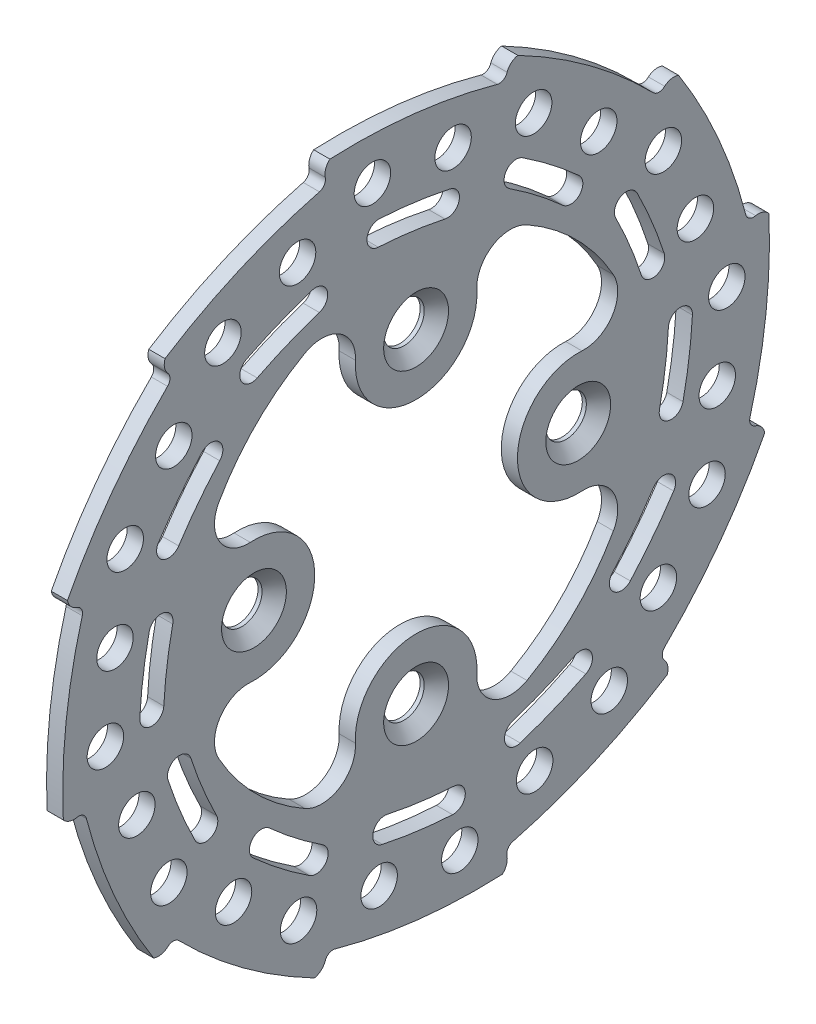
SolidWorks part; units mm, degrees
ref_plane "Front Plane" through (0, 0, 0) normal (0, 0, 1) x (1, 0, 0)
ref_plane "Top Plane" through (0, 0, 0) normal (0, 1, 0) x (1, 0, 0)
ref_plane "Right Plane" through (0, 0, 0) normal (1, 0, 0) x (0, 0, -1)
ref_plane "Plane1" through (4, 0, 0) normal (1, 0, 0) x (0, 0, -1)
sketch "Sketch1" plane through (4, 0, 0) normal (1, 0, 0) x (0, 0, -1)
  line L0 (-83.4912, 22.3714) -> (-83.7497, 22.4407)
  line L1 (-83.4912, -22.3714) -> (-83.7497, -22.4407)
  line L2 (-61.1198, -61.1198) -> (-61.3091, -61.3091)
  line L3 (-22.3714, -83.4912) -> (-22.4407, -83.7497)
  line L4 (22.3714, -83.4912) -> (22.4407, -83.7497)
  line L5 (61.1198, -61.1198) -> (61.3091, -61.3091)
  line L6 (83.4912, -22.3714) -> (83.7497, -22.4407)
  line L7 (83.4912, 22.3714) -> (83.7497, 22.4407)
  line L8 (61.1198, 61.1198) -> (61.3091, 61.3091)
  line L9 (22.3714, 83.4912) -> (22.4407, 83.7497)
  line L10 (-22.3714, 83.4912) -> (-22.4407, 83.7497)
  line L11 (-61.1198, 61.1198) -> (-61.3091, 61.3091)
  line L12 (0, 0) -> (-69.3199, -69.3199) construction
  circle A0 centre (40, 0) radius 5
  circle A1 centre (0, -40) radius 5
  circle A2 centre (-40, 0) radius 5
  circle A3 centre (-71.773, 28.9982) radius 4.5
  arc A4 (-52.8492, 40.1536) -> (-48.4456, 36.1774) centre (-50.6474, 38.1655) cw
  arc A5 (-48.4456, 36.1774) -> (-58.5717, 23.0439) centre (30.9131, -35.4797) ccw
  arc A6 (-58.5717, 23.0439) -> (-63.5372, 26.2913) centre (-61.0545, 24.6676) cw
  arc A7 (-63.5372, 26.2913) -> (-52.8492, 40.1536) centre (30.9131, -35.4797) cw
  circle A8 centre (-59.7785, 45.0463) radius 4.5
  circle A9 centre (-47.6581, 60.9996) radius 4.5
  arc A10 (-25.6919, 61.1987) -> (-23.8664, 55.5533) centre (-24.7791, 58.376) cw
  arc A11 (-23.8664, 55.5533) -> (-39.2027, 49.2424) centre (9.0317, -46.1828) ccw
  arc A12 (-39.2027, 49.2424) -> (-41.8792, 54.5376) centre (-40.5409, 51.89) cw
  arc A13 (-41.8792, 54.5376) -> (-25.6919, 61.1987) centre (9.0317, -46.1828) cw
  circle A14 centre (-29.2465, 68.9005) radius 4.5
  circle A15 centre (-10.7733, 76.6563) radius 4.5
  arc A16 (8.3495, 65.8455) -> (7.1078, 60.0438) centre (7.7286, 62.9447) cw
  arc A17 (7.1078, 60.0438) -> (-9.3293, 62.2465) centre (-15.2698, -44.5113) ccw
  arc A18 (-9.3293, 62.2465) -> (-8.9996, 68.1705) centre (-9.1645, 65.2085) cw
  arc A19 (-8.9996, 68.1705) -> (8.3495, 65.8455) centre (-15.2698, -44.5113) cw
  circle A20 centre (9.122, 74.2929) radius 4.5
  circle A21 centre (28.9982, 71.773) radius 4.5
  arc A22 (40.1536, 52.8492) -> (36.1774, 48.4456) centre (38.1655, 50.6474) cw
  arc A23 (36.1774, 48.4456) -> (23.0439, 58.5717) centre (-35.4797, -30.9131) ccw
  arc A24 (23.0439, 58.5717) -> (26.2913, 63.5372) centre (24.6676, 61.0545) cw
  arc A25 (26.2913, 63.5372) -> (40.1536, 52.8492) centre (-35.4797, -30.9131) cw
  circle A26 centre (45.0463, 59.7785) radius 4.5
  circle A27 centre (60.9996, 47.6581) radius 4.5
  arc A28 (61.1987, 25.6919) -> (55.5533, 23.8664) centre (58.376, 24.7791) cw
  arc A29 (55.5533, 23.8664) -> (49.2424, 39.2027) centre (-46.1828, -9.0317) ccw
  arc A30 (49.2424, 39.2027) -> (54.5376, 41.8792) centre (51.89, 40.5409) cw
  arc A31 (54.5376, 41.8792) -> (61.1987, 25.6919) centre (-46.1828, -9.0317) cw
  circle A32 centre (68.9005, 29.2465) radius 4.5
  circle A33 centre (76.6563, 10.7733) radius 4.5
  arc A34 (65.8455, -8.3495) -> (60.0438, -7.1078) centre (62.9447, -7.7286) cw
  arc A35 (60.0438, -7.1078) -> (62.2465, 9.3293) centre (-44.5113, 15.2698) ccw
  arc A36 (62.2465, 9.3293) -> (68.1705, 8.9996) centre (65.2085, 9.1645) cw
  arc A37 (68.1705, 8.9996) -> (65.8455, -8.3495) centre (-44.5113, 15.2698) cw
  circle A38 centre (74.2929, -9.122) radius 4.5
  circle A39 centre (71.773, -28.9982) radius 4.5
  arc A40 (52.8492, -40.1536) -> (48.4456, -36.1774) centre (50.6474, -38.1655) cw
  arc A41 (48.4456, -36.1774) -> (58.5717, -23.0439) centre (-30.9131, 35.4797) ccw
  arc A42 (58.5717, -23.0439) -> (63.5372, -26.2913) centre (61.0545, -24.6676) cw
  arc A43 (63.5372, -26.2913) -> (52.8492, -40.1536) centre (-30.9131, 35.4797) cw
  circle A44 centre (59.7785, -45.0463) radius 4.5
  circle A45 centre (47.6581, -60.9996) radius 4.5
  arc A46 (25.6919, -61.1987) -> (23.8664, -55.5533) centre (24.7791, -58.376) cw
  arc A47 (23.8664, -55.5533) -> (39.2027, -49.2424) centre (-9.0317, 46.1828) ccw
  arc A48 (39.2027, -49.2424) -> (41.8792, -54.5376) centre (40.5409, -51.89) cw
  arc A49 (41.8792, -54.5376) -> (25.6919, -61.1987) centre (-9.0317, 46.1828) cw
  circle A50 centre (29.2465, -68.9005) radius 4.5
  circle A51 centre (10.7733, -76.6563) radius 4.5
  arc A52 (-8.3495, -65.8455) -> (-7.1078, -60.0438) centre (-7.7286, -62.9447) cw
  arc A53 (-7.1078, -60.0438) -> (9.3293, -62.2465) centre (15.2698, 44.5113) ccw
  arc A54 (9.3293, -62.2465) -> (8.9996, -68.1705) centre (9.1645, -65.2085) cw
  arc A55 (8.9996, -68.1705) -> (-8.3495, -65.8455) centre (15.2698, 44.5113) cw
  circle A56 centre (-9.122, -74.2929) radius 4.5
  circle A57 centre (-28.9982, -71.773) radius 4.5
  arc A58 (-40.1536, -52.8492) -> (-36.1774, -48.4456) centre (-38.1655, -50.6474) cw
  arc A59 (-36.1774, -48.4456) -> (-23.0439, -58.5717) centre (35.4797, 30.9131) ccw
  arc A60 (-23.0439, -58.5717) -> (-26.2913, -63.5372) centre (-24.6676, -61.0545) cw
  arc A61 (-26.2913, -63.5372) -> (-40.1536, -52.8492) centre (35.4797, 30.9131) cw
  circle A62 centre (-45.0463, -59.7785) radius 4.5
  circle A63 centre (-60.9996, -47.6581) radius 4.5
  arc A64 (-54.5376, -41.8792) -> (-61.1987, -25.6919) centre (46.1828, 9.0317) cw
  arc A65 (-61.1987, -25.6919) -> (-55.5533, -23.8664) centre (-58.376, -24.7791) cw
  arc A66 (-55.5533, -23.8664) -> (-49.2424, -39.2027) centre (46.1828, 9.0317) ccw
  arc A67 (-49.2424, -39.2027) -> (-54.5376, -41.8792) centre (-51.89, -40.5409) cw
  circle A68 centre (-68.9005, -29.2465) radius 4.5
  arc A69 (-65.8455, 8.3495) -> (-60.0438, 7.1078) centre (-62.9447, 7.7286) cw
  arc A70 (-60.0438, 7.1078) -> (-62.2465, -9.3293) centre (44.5113, -15.2698) ccw
  arc A71 (-62.2465, -9.3293) -> (-68.1705, -8.9996) centre (-65.2085, -9.1645) cw
  arc A72 (-68.1705, -8.9996) -> (-65.8455, 8.3495) centre (44.5113, -15.2698) cw
  circle A73 centre (-76.6563, -10.7733) radius 4.5
  circle A74 centre (-74.2929, 9.122) radius 4.5
  circle A75 centre (0, 40) radius 5
  circle A76 centre (40, 0) radius 15
  arc A77 (-40.9088, 14.9724) -> (-48.6744, 27.3701) centre (-41.4135, 23.2872) cw
  arc A78 (-48.6744, 27.3701) -> (-27.3701, 48.6744) centre (0, 0) cw
  arc A79 (-14.9724, 40.9088) -> (-27.3701, 48.6744) centre (-23.2872, 41.4135) ccw
  circle A80 centre (0, -40) radius 15
  arc A81 (-14.9724, -40.9088) -> (-27.3701, -48.6744) centre (-23.2872, -41.4135) cw
  arc A82 (-27.3701, -48.6744) -> (-48.6744, -27.3701) centre (0, 0) cw
  arc A83 (14.9724, 40.9088) -> (27.3701, 48.6744) centre (23.2872, 41.4135) cw
  circle A84 centre (-40, 0) radius 15
  arc A85 (27.3701, 48.6744) -> (48.6744, 27.3701) centre (0, 0) cw
  arc A86 (40.9088, 14.9724) -> (48.6744, 27.3701) centre (41.4135, 23.2872) ccw
  arc A87 (40.9088, -14.9724) -> (48.6744, -27.3701) centre (41.4135, -23.2872) cw
  arc A88 (-40.9088, -14.9724) -> (-48.6744, -27.3701) centre (-41.4135, -23.2872) ccw
  arc A89 (48.6744, -27.3701) -> (27.3701, -48.6744) centre (0, 0) cw
  arc A90 (14.9724, -40.9088) -> (27.3701, -48.6744) centre (23.2872, -41.4135) ccw
  arc A92 (-86.0187, 25.093) -> (-83.4912, 22.3714) centre (-82.5871, 25.7454) ccw
  arc A93 (-83.7497, 22.4407) -> (-82.3634, 20.0131) centre (-84.259, 20.5402) cw
  arc A94 (-82.3634, 20.0131) -> (-87.0409, -21.2781) centre (44.5113, -15.2698) ccw
  arc A95 (-87.0409, -21.2781) -> (-83.4912, -22.3714) centre (-84.3952, -18.9974) ccw
  arc A96 (-83.7497, -22.4407) -> (-81.3354, -23.8499) centre (-83.2405, -24.3411) cw
  arc A97 (-81.3354, -23.8499) -> (-64.7405, -61.9478) centre (46.1828, 9.0317) ccw
  arc A98 (-64.7405, -61.9478) -> (-61.1198, -61.1198) centre (-63.5897, -58.6498) ccw
  arc A99 (-61.3091, -61.3091) -> (-58.5136, -61.3223) centre (-59.9178, -62.7003) cw
  arc A100 (-58.5136, -61.3223) -> (-25.093, -86.0187) centre (35.4797, 30.9131) ccw
  arc A101 (-25.093, -86.0187) -> (-22.3714, -83.4912) centre (-25.7454, -82.5871) ccw
  arc A102 (-22.4407, -83.7497) -> (-20.0131, -82.3634) centre (-20.5402, -84.259) cw
  arc A103 (-20.0131, -82.3634) -> (21.2781, -87.0409) centre (15.2698, 44.5113) ccw
  arc A104 (21.2781, -87.0409) -> (22.3714, -83.4912) centre (18.9974, -84.3952) ccw
  arc A105 (22.4407, -83.7497) -> (23.8499, -81.3354) centre (24.3411, -83.2405) cw
  arc A106 (23.8499, -81.3354) -> (61.9478, -64.7405) centre (-9.0317, 46.1828) ccw
  arc A107 (61.9478, -64.7405) -> (61.1198, -61.1198) centre (58.6498, -63.5897) ccw
  arc A108 (61.3091, -61.3091) -> (61.3223, -58.5136) centre (62.7003, -59.9178) cw
  arc A109 (61.3223, -58.5136) -> (86.0187, -25.093) centre (-30.9131, 35.4797) ccw
  arc A110 (86.0187, -25.093) -> (83.4912, -22.3714) centre (82.5871, -25.7454) ccw
  arc A111 (83.7497, -22.4407) -> (82.3634, -20.0131) centre (84.259, -20.5402) cw
  arc A112 (82.3634, -20.0131) -> (87.0409, 21.2781) centre (-44.5113, 15.2698) ccw
  arc A113 (87.0409, 21.2781) -> (83.4912, 22.3714) centre (84.3952, 18.9974) ccw
  arc A114 (83.7497, 22.4407) -> (81.3354, 23.8499) centre (83.2405, 24.3411) cw
  arc A115 (81.3354, 23.8499) -> (64.7405, 61.9478) centre (-46.1828, -9.0317) ccw
  arc A116 (64.7405, 61.9478) -> (61.1198, 61.1198) centre (63.5897, 58.6498) ccw
  arc A117 (61.3091, 61.3091) -> (58.5136, 61.3223) centre (59.9178, 62.7003) cw
  arc A118 (58.5136, 61.3223) -> (25.093, 86.0187) centre (-35.4797, -30.9131) ccw
  arc A119 (25.093, 86.0187) -> (22.3714, 83.4912) centre (25.7454, 82.5871) ccw
  arc A120 (22.4407, 83.7497) -> (20.0131, 82.3634) centre (20.5402, 84.259) cw
  arc A121 (20.0131, 82.3634) -> (-21.2781, 87.0409) centre (-15.2698, -44.5113) ccw
  arc A122 (-21.2781, 87.0409) -> (-22.3714, 83.4912) centre (-18.9974, 84.3952) ccw
  arc A123 (-22.4407, 83.7497) -> (-23.8499, 81.3354) centre (-24.3411, 83.2405) cw
  arc A124 (-23.8499, 81.3354) -> (-61.9478, 64.7405) centre (9.0317, -46.1828) ccw
  arc A125 (-61.9478, 64.7405) -> (-61.1198, 61.1198) centre (-58.6498, 63.5897) ccw
  arc A126 (-61.3091, 61.3091) -> (-61.3223, 58.5136) centre (-62.7003, 59.9178) cw
  arc A127 (-61.3223, 58.5136) -> (-86.0187, 25.093) centre (30.9131, -35.4797) ccw
  circle A128 centre (0, 40) radius 15
  point P247 (0, 0)
  point P253 (0, 0)
  dimension "D2" = 4
  dimension "D5" = 10
  dimension "D6" = 10
  dimension "D7" = 10
  dimension "D8" = 10
  dimension "D12" = 30
  dimension "D3" = 40
  dimension "D4" = 40
  dimension "D9" = 56.5685
  dimension "D10" = 56.5685
  dimension "D13" = 4
extrude "Boss-Extrude1" add sketch "Sketch1" along normal blind 4
chamfer "Chamfer1" distance 3 angle 45 4 edges at (8, 0, 35) (8, -40, -5) (8, 0, -45) (8, 40, -5)
